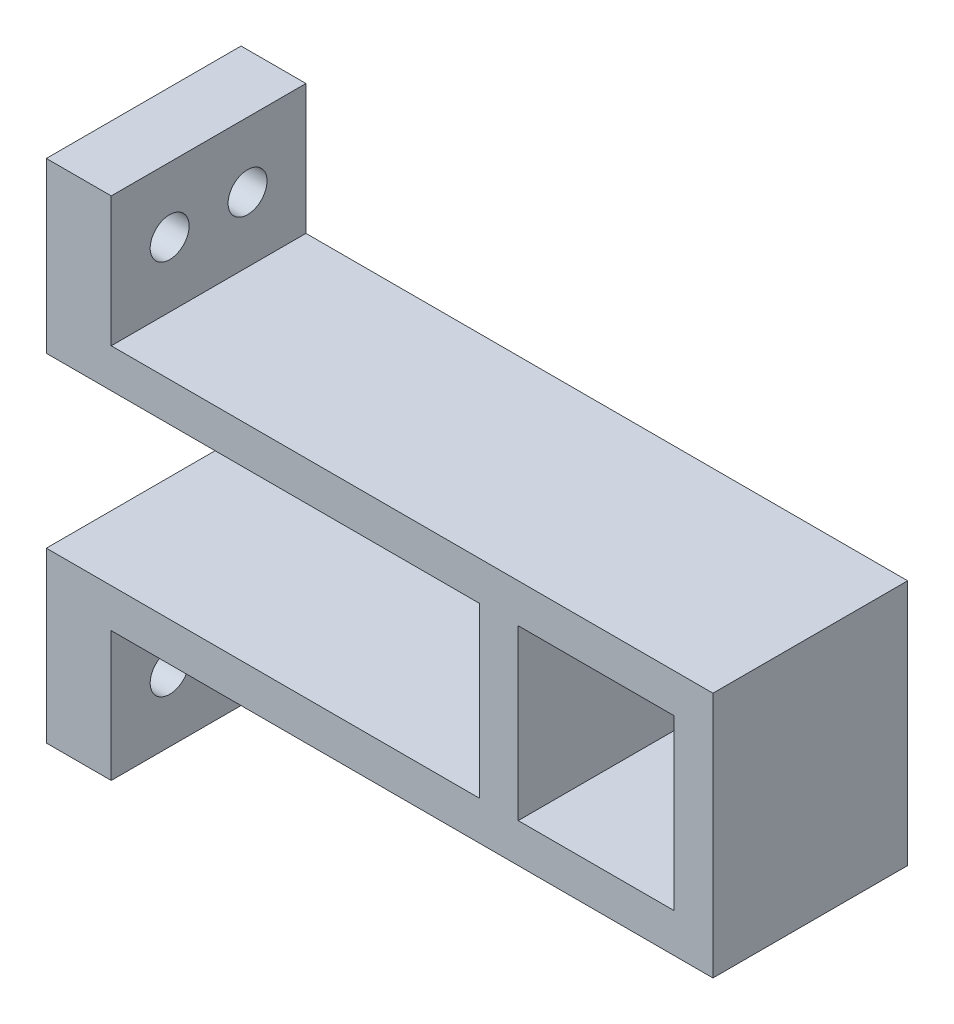
SolidWorks part; units mm, degrees
ref_plane "Front Plane" through (0, 0, 0) normal (0, 0, 1) x (1, 0, 0)
ref_plane "Top Plane" through (0, 0, 0) normal (0, 1, 0) x (1, 0, 0)
ref_plane "Right Plane" through (0, 0, 0) normal (1, 0, 0) x (0, 0, -1)
sketch "Sketch1" plane through (0, 0, 0) normal (1, 0, 0) x (0, 0, -1)
  line L1 (0, 0) -> (15, 0)
  line L2 (0, 0) -> (0, 13)
  line L3 (0, 13) -> (15, 13)
  line L4 (15, 0) -> (15, 13)
  line L5 (0, 26) -> (15, 26)
  line L6 (0, 26) -> (0, 39)
  line L7 (0, 39) -> (15, 39)
  line L8 (15, 26) -> (15, 39)
  circle A0 centre (4.5, 34) radius 1.5
  circle A1 centre (10.5, 34) radius 1.5
  circle A2 centre (4.5, 5) radius 1.5
  circle A3 centre (10.5, 5) radius 1.5
  dimension "D6" = 3
  dimension "D7" = 3
  dimension "D12" = 3
  dimension "D13" = 3
  dimension "D1" = 13
  dimension "D2" = 15
  dimension "D3" = 13
  dimension "D4" = 15
  dimension "D5" = 13
  dimension "D8" = 4.5
  dimension "D9" = 6
  dimension "D10" = 4.5
  dimension "D11" = 6
  dimension "D14" = 5
  dimension "D15" = 5
extrude "Boss-Extrude1" add sketch "Sketch1" along normal blind 5
sketch "Sketch2" plane through (5, 0, 0) normal (1, 0, 0) x (0, 0, -1)
  line L0 (15, 26) -> (15, 39) construction
  line L1 (0, 26) -> (15, 26)
  line L2 (0, 26) -> (0, 29)
  line L3 (0, 29) -> (15, 29)
  line L4 (15, 26) -> (15, 29)
  line L6 (0, 13) -> (15, 13)
  line L7 (0, 13) -> (0, 10)
  line L8 (0, 10) -> (15, 10)
  line L9 (15, 13) -> (15, 10)
  dimension "D1" = 3
  dimension "D2" = 3
extrude "Boss-Extrude2" add sketch "Sketch2" along normal blind 43.35
sketch "Sketch3" plane through (48.35, 0, 0) normal (1, 0, 0) x (0, 0, -1)
  line L1 (0, 29) -> (15, 29)
  line L2 (0, 29) -> (0, 10)
  line L3 (0, 10) -> (15, 10)
  line L4 (15, 29) -> (15, 10)
extrude "Boss-Extrude3" add sketch "Sketch3" along normal blind 3
sketch "Sketch5" plane through (51.35, 0, 0) normal (1, 0, 0) x (0, 0, -1)
  line L1 (0, 29) -> (15, 29)
  line L2 (0, 29) -> (0, 10)
  line L3 (0, 10) -> (15, 10)
  line L4 (15, 29) -> (15, 10)
extrude "Boss-Extrude5" add sketch "Sketch5" against normal blind 3 from offset 15 offset against normal yes
sketch "Sketch7" plane through (51.35, 0, 0) normal (1, 0, 0) x (0, 0, -1)
  line L1 (0, 29) -> (0, 10) construction
  line L2 (0, 18) -> (15, 18)
  line L3 (0, 18) -> (0, 20)
  line L4 (0, 20) -> (15, 20)
  line L6 (15, 18) -> (15, 20)
  line L7 (15, 10) -> (15, 29) construction
  line L8 (0, 10) -> (15, 10) construction
  dimension "D1" = 2
  dimension "D2" = 8
